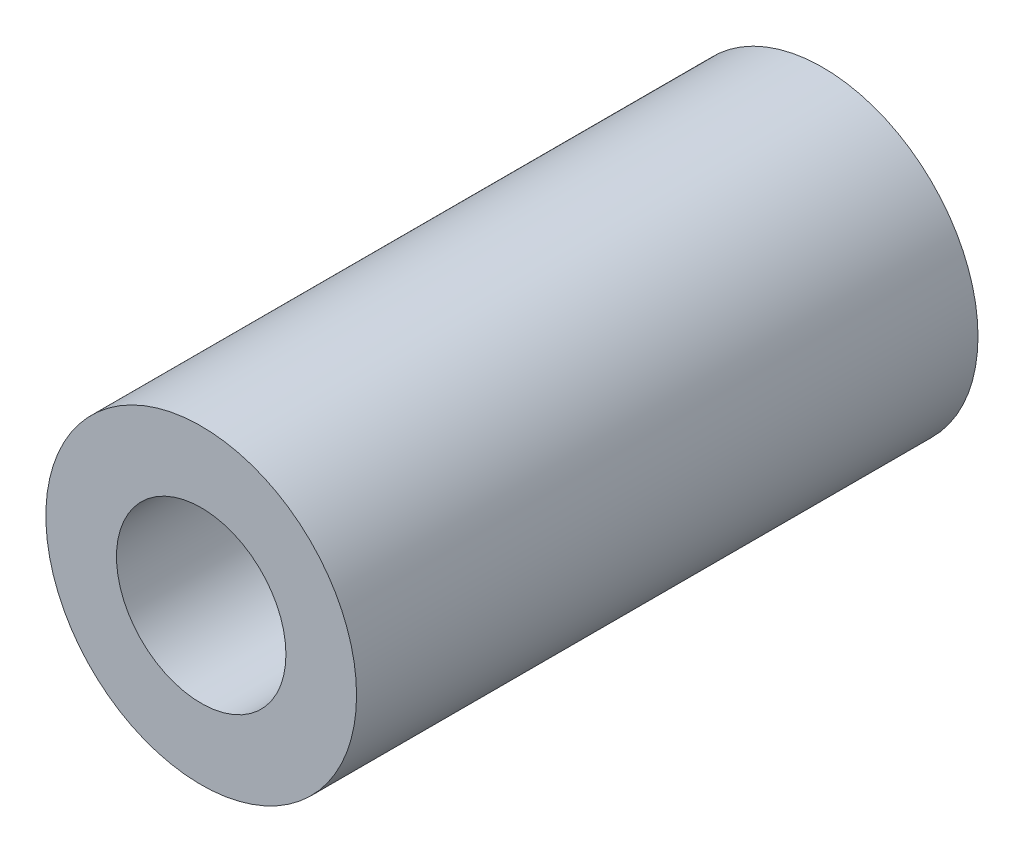
SolidWorks part; units mm, degrees
ref_plane "Front" through (0, 0, 0) normal (0, 0, 1) x (1, 0, 0)
ref_plane "Top" through (0, 0, 0) normal (0, 1, 0) x (1, 0, 0)
ref_plane "Right" through (0, 0, 0) normal (1, 0, 0) x (0, 0, -1)
sketch "Эскиз1" plane through (0, 0, 0) normal (0, 0, 1) x (1, 0, 0)
  circle A0 centre (0, 0) radius 1.5
  circle A1 centre (0, 0) radius 2.75
  dimension "D1" = 5.5
  dimension "D2" = 3
extrude "Бобышка-Вытянуть1" add sketch "Эскиз1" along normal blind 11
